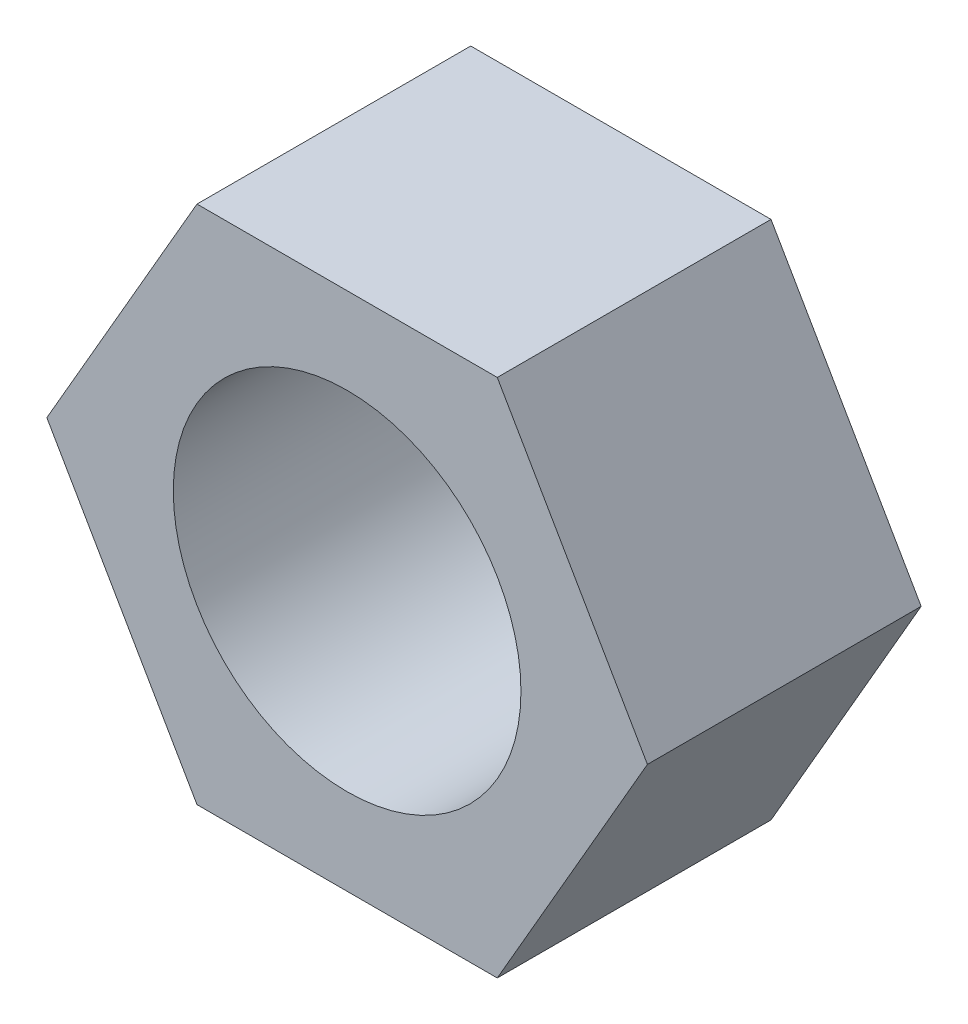
SolidWorks part; units mm, degrees
material "AISI 4340 Acero normalizado"
ref_plane "Alzado" through (0, 0, 0) normal (0, 0, 1) x (1, 0, 0)
ref_plane "Planta" through (0, 0, 0) normal (0, 1, 0) x (1, 0, 0)
ref_plane "Vista lateral" through (0, 0, 0) normal (1, 0, 0) x (0, 0, -1)
sketch "Croquis1" plane through (0, 0, 0) normal (0, 0, 1) x (1, 0, 0)
  circle A0 centre (0, 0) radius 6.35
extrude "Saliente-Extruir1" add sketch "Croquis1" along normal blind 30
sketch "Croquis2" plane through (0, 0, 30) normal (0, 0, 1) x (1, 0, 0)
  line L1 (10.9697, 0) -> (5.4848, 9.5)
  line L2 (5.4848, 9.5) -> (-5.4848, 9.5)
  line L3 (-5.4848, 9.5) -> (-10.9697, 0)
  line L4 (-10.9697, 0) -> (-5.4848, -9.5)
  line L5 (-5.4848, -9.5) -> (5.4848, -9.5)
  line L6 (5.4848, -9.5) -> (10.9697, 0)
  circle A0 centre (0, 0) radius 9.5 construction
  dimension "D1" = 19
extrude "Saliente-Extruir2" add sketch "Croquis2" along normal blind 10
sketch "Croquis4" plane through (0, 0, 0) normal (0, 0, -1) x (-1, 0, 0)
  circle A1 centre (0, 0) radius 6.35
  circle A2 centre (0, 0) radius 6.35
  dimension "D1" = 0
extrude "Cortar-Extruir1" cut sketch "Croquis4" against normal through all
